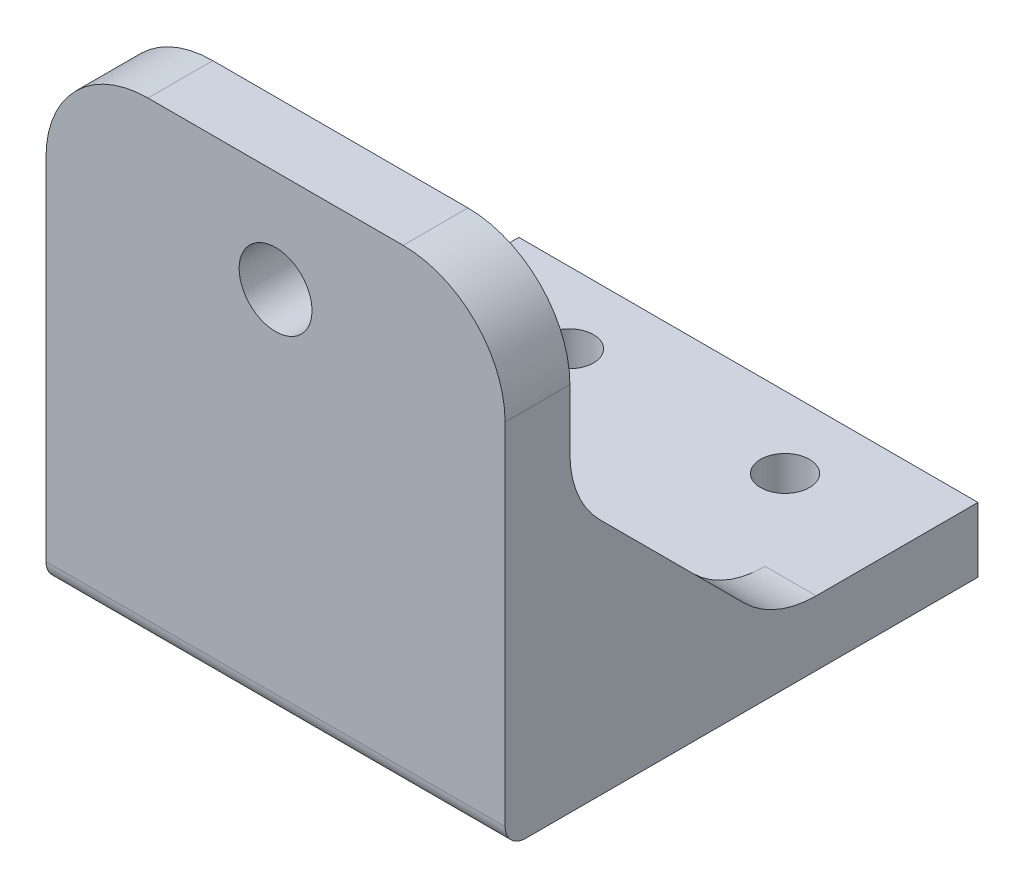
SolidWorks part; units mm, degrees
material "ABS PC"
ref_plane "Front Plane" through (0, 0, 0) normal (0, 0, 1) x (1, 0, 0)
ref_plane "Top Plane" through (0, 0, 0) normal (0, 1, 0) x (1, 0, 0)
ref_plane "Right Plane" through (0, 0, 0) normal (1, 0, 0) x (0, 0, -1)
sketch "Sketch1" plane through (0, 0, 0) normal (0, 1, 0) x (1, 0, 0)
  line L5 (-22.5, -77.5) -> (22.5, -77.5)
  line L6 (-22.5, -77.5) -> (-22.5, 0)
  line L8 (22.5, -77.5) -> (22.5, 0)
  line L9 (-22.5, -77.5) -> (22.5, 0) construction
  line L10 (-22.5, 0) -> (22.5, -77.5) construction
  arc A0 (22.5, 0) -> (-22.5, 0) centre (0, 0) ccw
  point P2 (0, -38.75)
  dimension "D1" = 45
  dimension "D2" = 100
  dimension "D3" = 45
extrude "Boss-Extrude1" add sketch "Sketch1" along normal blind 6.35
sketch "Sketch2" plane through (0, 6.35, 0) normal (0, 1, 0) x (1, 0, 0)
  line L0 (-6.697, 16.1679) -> (6.697, 16.1679) construction
  circle A0 centre (0, 0) radius 17.5 construction
  circle A1 centre (0, 0) radius 17.5 construction
  circle A2 centre (0, 0) radius 17.5 construction
  circle A3 centre (0, 0) radius 17.5 construction
  circle A4 centre (0, 0) radius 17.5 construction
  circle A5 centre (0, 0) radius 17.5 construction
  circle A6 centre (0, 0) radius 17.5 construction
  circle A7 centre (0, 0) radius 17.5 construction
  point P3 (-6.697, 16.1679)
  point P5 (-16.1679, -6.697)
  point P7 (6.697, 16.1679)
  point P9 (16.1679, 6.697)
  point P11 (16.1679, -6.697)
  point P13 (6.697, -16.1679)
  point P15 (-6.697, -16.1679)
  point P16 (0, 0)
  point P18 (-16.1679, 6.697)
  dimension "D1" = 35
  dimension "D2" = 8
hole_wizard "M5 Clearance Hole1" positions "Sketch3" profile "Sketch4" hole size "M5" standard "ANSI Metric" end condition through all
sketch "Sketch3" plane through (0, 6.35, 0) normal (0, 1, 0) x (1, 0, 0)
  point P0 (-6.697, -16.1679)
  point P3 (6.697, -16.1679)
  point P6 (6.697, 16.1679)
  point P15 (-6.697, 16.1679)
sketch "Sketch4" plane through (-6.697, 6.35, 16.1679) normal (1, 0, 0) x (0, 0, 1)
  line L0 (0, 0) -> (0, 6.35)
  line L1 (0, 6.35) -> (2.75, 6.35)
  line L2 (2.75, 6.35) -> (2.75, 0.025)
  line L3 (2.75, 0.025) -> (2.775, 0)
  line L5 (2.775, 0) -> (0, 0)
  line L6 (-2.75, 0.025) -> (-2.775, 0) construction
  line L11 (0, -6.35) -> (0, 107.95) construction
  dimension "Thru Hole Dia." = 5.5
  dimension "Thru Hole Depth" = 6.35
  dimension "Near C'Sink Dia." = 5.55
  dimension "Near C'Sink Angle" = 90
sketch "Sketch5" plane through (0, 6.35, 0) normal (0, 1, 0) x (1, 0, 0)
  circle A0 centre (0, 0) radius 12.5
  dimension "D1" = 25
extrude "Cut-Extrude1" cut sketch "Sketch5" against normal through all
sketch "Sketch6" [suppressed] plane through (0, 6.35, 0) normal (0, 1, 0) x (1, 0, 0)
  line L0 (-22.5, -77.5) -> (22.5, -77.5) construction
  circle A0 centre (0, -71) radius 3.3782
  dimension "D1" = 6.7564
  dimension "D2" = 6.5
sketch "Sketch7" [suppressed] plane through (0, 6.35, 0) normal (0, 1, 0) x (1, 0, 0)
  line L0 (12.5, -58.5) -> (-12.5, -58.5) construction
  line L1 (12.5, -63) -> (-12.5, -63)
  line L2 (12.5, -54) -> (-12.5, -54)
  line L3 (0, -71) -> (0, 0) construction
  line L4 (12.5, -42.5) -> (-12.5, -42.5) construction
  line L5 (12.5, -47) -> (-12.5, -47)
  line L6 (12.5, -38) -> (-12.5, -38)
  line L7 (12.5, -26.5) -> (-12.5, -26.5) construction
  line L8 (12.5, -31) -> (-12.5, -31)
  line L9 (12.5, -22) -> (-12.5, -22)
  arc A0 (12.5, -63) -> (12.5, -54) centre (12.5, -58.5) ccw
  arc A1 (-12.5, -54) -> (-12.5, -63) centre (-12.5, -58.5) ccw
  arc A2 (12.5, -47) -> (12.5, -38) centre (12.5, -42.5) ccw
  arc A3 (-12.5, -38) -> (-12.5, -47) centre (-12.5, -42.5) ccw
  arc A4 (12.5, -31) -> (12.5, -22) centre (12.5, -26.5) ccw
  arc A5 (-12.5, -22) -> (-12.5, -31) centre (-12.5, -26.5) ccw
  circle A6 centre (0, -71) radius 3.3782 construction
  point P2 (0, -58.5)
  point P15 (0, -42.5)
  point P22 (0, -26.5)
  point P28 (0, -63)
  dimension "D2" = 4.5
  dimension "D4" = 8
  dimension "D3" = 25
  dimension "D1" = 3
extrude "Cut-Extrude3" [suppressed] cut sketch "Sketch7" against normal through all
sketch "Sketch12" plane through (0, 0, 77.5) normal (0, 0, 1) x (1, 0, 0)
  line L0 (-22.5, 6.35) -> (22.5, 6.35) construction
  line L1 (22.5, 0) -> (-22.5, 0)
  line L2 (22.5, 0) -> (22.5, 46.35)
  line L3 (22.5, 46.35) -> (-22.5, 46.35)
  line L4 (-22.5, 0) -> (-22.5, 46.35)
  dimension "D1" = 40
extrude "Boss-Extrude2" add sketch "Sketch12" along normal blind 6.35
sketch "Sketch13" plane through (0, 0, 77.5) normal (0, 0, -1) x (-1, 0, 0)
  line L0 (22.5, 6.35) -> (-22.5, 6.35) construction
  point P0 (0, 36.35)
  dimension "D1" = 30
hole_wizard "1/4 Clearance Hole1" positions "Sketch16" profile "Sketch17" hole size "1/4" standard "ANSI Inch" end condition through all
sketch "Sketch16" plane through (0, 0, 77.5) normal (0, 0, -1) x (-1, 0, 0)
  point P0 (0, 36.35)
sketch "Sketch17" plane through (0, 36.35, 77.5) normal (1, 0, 0) x (0, 1, 0)
  line L0 (0, 0) -> (0, 6.35)
  line L1 (0, 6.35) -> (3.5712, 6.35)
  line L2 (3.5712, 6.35) -> (3.5712, 0.635)
  line L3 (3.5712, 0.635) -> (4.2062, 0)
  line L5 (4.2062, 0) -> (0, 0)
  line L6 (-3.5712, 0.635) -> (-4.2062, 0) construction
  line L11 (0, -6.35) -> (0, 107.95) construction
  dimension "Thru Hole Dia." = 7.1425
  dimension "Thru Hole Depth" = 6.35
  dimension "Near C'Sink Dia." = 8.4125
  dimension "Near C'Sink Angle" = 90
fillet "Fillet1" radius 10 2 edges at (-22.5, 46.35, 80.675) (22.5, 46.35, 80.675)
fillet "Fillet2" radius 2 2 edges at (0, 0, 83.85) (0, 6.35, 77.5)
ref_plane "Plane1" through (0, 0, -22.5) normal (0, 0, 1) x (1, 0, 0)
sketch "Sketch18" plane through (0, 0, -22.5) normal (0, 0, 1) x (1, 0, 0)
  line L1 (-32.4973, -4.485) -> (73.8257, -4.485)
  line L2 (-32.4973, -4.485) -> (-32.4973, 66.5178)
  line L3 (-32.4973, 66.5178) -> (73.8257, 66.5178)
  line L4 (73.8257, -4.485) -> (73.8257, 66.5178)
extrude "Cut-Extrude4" cut sketch "Sketch18" along normal blind 60
sketch "Sketch19" plane through (0, 0, 0) normal (0, -1, 0) x (1, 0, 0)
  line L0 (-10.5848, 44.5) -> (10.5848, 44.5) construction
  line L1 (22.5, 37.5) -> (-22.5, 37.5) construction
  point P2 (0, 44.5)
  point P5 (0, 37.5)
  dimension "D1" = 7
  dimension "D2" = 21.1696
hole_wizard "M4 Clearance Hole1" positions "Sketch20" profile "Sketch21" hole size "M4" standard "ANSI Metric" end condition through all
sketch "Sketch20" plane through (0, 0, 0) normal (0, -1, 0) x (-1, 0, 0)
  point P0 (10.5848, -44.5)
  point P3 (-10.5848, -44.5)
sketch "Sketch21" plane through (-10.5848, 0, 44.5) normal (1, 0, 0) x (0, 0, -1)
  line L0 (0, 0) -> (0, 46.35)
  line L1 (0, 46.35) -> (2.4, 46.35)
  line L2 (2.4, 46.35) -> (2.4, 0)
  line L5 (2.4, 0) -> (0, 0)
  line L11 (0, -6.35) -> (0, 107.95) construction
  dimension "Thru Hole Dia." = 4.8
  dimension "Thru Hole Depth" = 46.35
sketch "Sketch23" plane through (-22.5, 0, 0) normal (-1, 0, 0) x (0, 0, 1)
  line L0 (77.5, 26.35) -> (57.5, 6.35)
  line L1 (77.5, 36.35) -> (77.5, 8.35) construction
  line L2 (37.5, 6.35) -> (75.5, 6.35) construction
  line L3 (57.5, 6.35) -> (77.5, 6.35)
  line L4 (77.5, 6.35) -> (77.5, 26.35)
  dimension "D1" = 20
  dimension "D2" = 20
extrude "Boss-Extrude3" add sketch "Sketch23" against normal blind 5
fillet "Fillet3" radius 10 2 edges at (-20, 6.35, 57.5) (-20, 26.35, 77.5)
mirror "Mirror1" about plane through (0, 0, 0) normal (1, 0, 0) of "Boss-Extrude3", "Fillet3"
